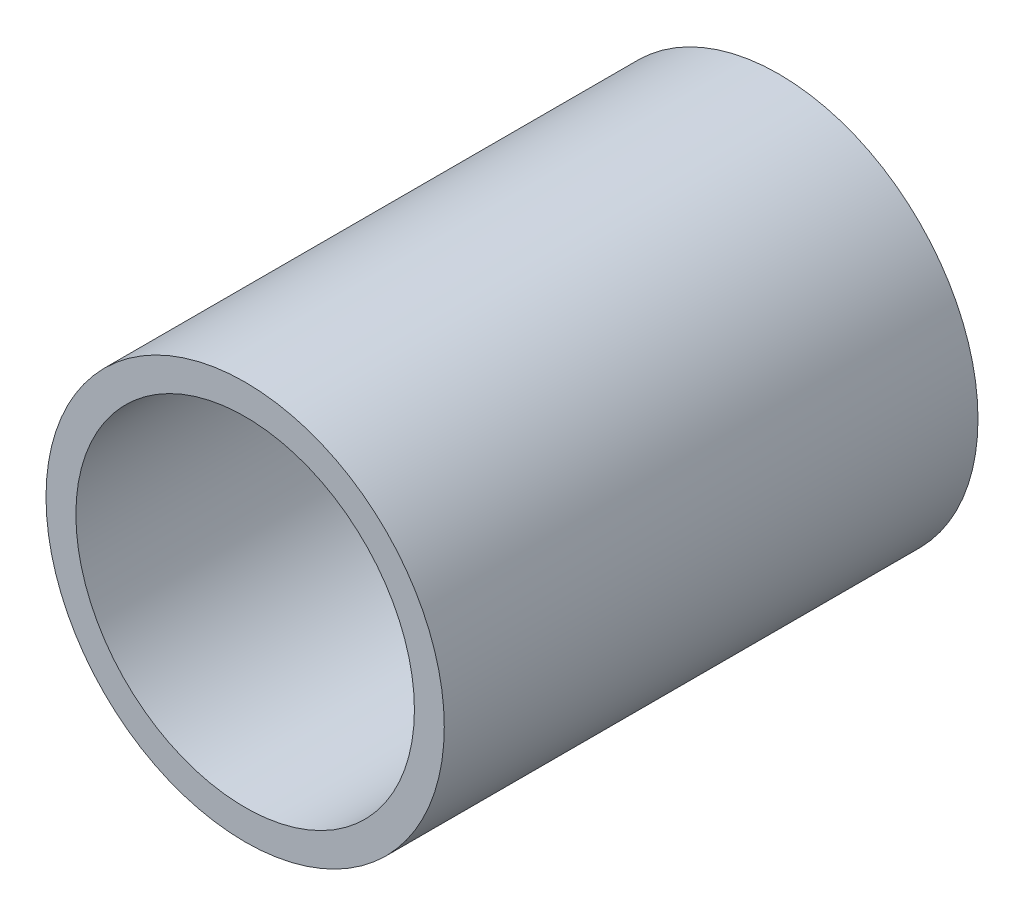
SolidWorks part; units mm, degrees
ref_plane "Front Plane" through (0, 0, 0) normal (0, 0, 1) x (1, 0, 0)
ref_plane "Top Plane" through (0, 0, 0) normal (0, 1, 0) x (1, 0, 0)
ref_plane "Right Plane" through (0, 0, 0) normal (1, 0, 0) x (0, 0, -1)
sketch "Sketch3" plane through (0, 0, 0) normal (0, 0, 1) x (1, 0, 0)
  circle A5 centre (0, 0) radius 50
  circle A7 centre (0, 0) radius 42.5
  dimension "D1" = 100
  dimension "D2" = 85
extrude "Boss-Extrude1" add sketch "Sketch3" along normal blind 134
